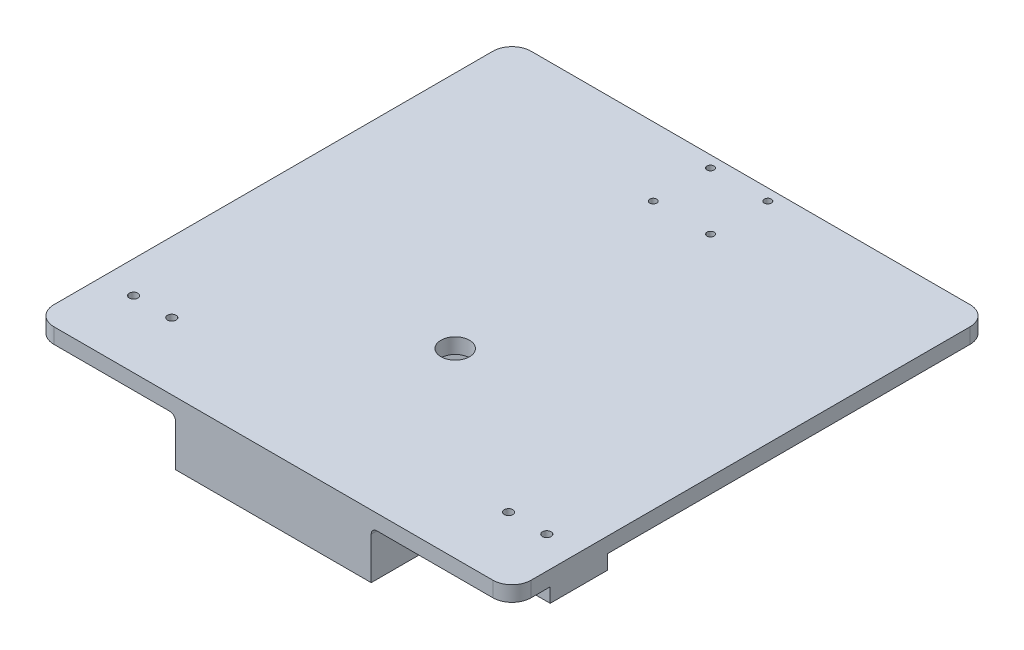
SolidWorks part; units mm, degrees
ref_plane "Front Plane" through (0, 0, 0) normal (0, 0, 1) x (1, 0, 0)
ref_plane "Top Plane" through (0, 0, 0) normal (0, 1, 0) x (1, 0, 0)
ref_plane "Right Plane" through (0, 0, 0) normal (1, 0, 0) x (0, 0, -1)
sketch "Sketch1" plane through (0, 0, 0) normal (0, 1, 0) x (1, 0, 0)
  line L1 (-125, 125) -> (125, 125)
  line L2 (-125, 125) -> (-125, -125)
  line L3 (-125, -125) -> (125, -125)
  line L4 (125, 125) -> (125, -125)
  line L5 (-125, 125) -> (125, -125) construction
  line L6 (-125, -125) -> (125, 125) construction
  point P0 (0, 0)
  dimension "D1" = 250
  dimension "D2" = 250
extrude "Boss-Extrude1" add sketch "Sketch1" along normal blind 8
sketch "Sketch2" plane through (0, 0, 0) normal (0, -1, 0) x (1, 0, 0)
  line L0 (-125, -125) -> (-125, 125) construction
  line L1 (-71.45, 75) -> (-125, 75)
  line L2 (-71.45, 75) -> (-71.45, 105)
  line L3 (-71.45, 105) -> (-125, 105)
  line L4 (-125, 75) -> (-125, 105)
  line L5 (-125, 105) -> (-119, 105) construction
  line L6 (125, 125) -> (125, -125) construction
  line L7 (71.45, 105) -> (125, 105)
  line L8 (71.45, 105) -> (71.45, 75)
  line L9 (71.45, 75) -> (125, 75)
  line L10 (125, 105) -> (125, 75)
  point P16 (0, 0)
  point P17 (71.45, 75)
extrude "Boss-Extrude2" add sketch "Sketch2" along normal up to surface (7.5 mm away)
sketch "Sketch3" plane through (0, -7.5, 0) normal (0, -1, 0) x (1, 0, 0)
  circle A0 centre (108.225, 90) radius 2.25
  circle A1 centre (88.225, 90) radius 2.25
  circle A2 centre (-108.225, 90) radius 2.25
  circle A3 centre (-88.225, 90) radius 2.25
extrude "Cut-Extrude1" cut sketch "Sketch3" against normal through all
sketch "Sketch4" plane through (0, 0, 0) normal (0, -1, 0) x (1, 0, 0)
  line L0 (0, 125) -> (-51.25, 125)
  line L1 (-48.25, 19.74) -> (0, 19.74) construction
  line L2 (-125, 125) -> (125, 125) construction
  line L3 (0, 122) -> (-48.25, 122) construction
  line L4 (-51.25, 125) -> (-51.25, 16.74)
  line L5 (-51.25, 16.74) -> (0, 16.74)
  line L8 (0, 125) -> (0, -101.2984) construction
  line L9 (-36.25, 112) -> (-36.25, 41.74) construction
  line L10 (-36.25, 41.74) -> (-2.5, 41.74) construction
  line L11 (0, 122) -> (-40.25, 122)
  line L12 (-48.25, 114) -> (-48.25, 27.74)
  line L13 (-40.25, 19.74) -> (0, 19.74)
  line L14 (0, 125) -> (0, -43.5626) construction
  line L15 (40.25, 19.74) -> (0, 19.74)
  line L16 (51.25, 16.74) -> (0, 16.74)
  line L17 (48.25, 114) -> (48.25, 27.74)
  line L18 (0, 122) -> (40.25, 122)
  line L19 (51.25, 125) -> (51.25, 16.74)
  line L20 (0, 125) -> (51.25, 125)
  line L21 (48.25, 70.87) -> (-48.25, 70.87) construction
  line L24 (48.25, 114) -> (40.25, 114)
  line L25 (40.25, 122) -> (40.25, 114)
  line L28 (-48.25, 114) -> (-40.25, 114)
  line L29 (-40.25, 122) -> (-40.25, 114)
  line L32 (-48.25, 27.74) -> (-40.25, 27.74)
  line L33 (-40.25, 19.74) -> (-40.25, 27.74)
  line L36 (48.25, 27.74) -> (40.25, 27.74)
  line L37 (40.25, 19.74) -> (40.25, 27.74)
  line L38 (-48.25, 122) -> (-48.25, 19.74) construction
  circle A0 centre (-44.25, 118) radius 1.5
  circle A1 centre (44.25, 118) radius 1.5
  circle A2 centre (44.25, 23.74) radius 1.5
  circle A3 centre (-44.25, 23.74) radius 1.5
  dimension "D12" = 3
  dimension "D2" = 25
  dimension "D3" = 3
  dimension "D1" = 15
  dimension "D4" = 8
  dimension "D5" = 8
  dimension "D6" = 8
  dimension "D7" = 8
  dimension "D8" = 8
  dimension "D9" = 8
  dimension "D10" = 8
  dimension "D11" = 8
extrude "Boss-Extrude3" add sketch "Sketch4" along normal blind 25
fillet "Fillet1" radius 3 5 edges at (51.25, -12.5, 16.74) (-51.25, -12.5, 16.74) (0, 0, 16.74) (51.25, 0, 70.87) (-51.25, 0, 70.87)
sketch "Sketch5" plane through (-51.25, 0, 0) normal (-1, 0, 0) x (0, 0, 1)
  line L0 (72.37, -3) -> (72.37, -25) construction
  line L1 (125, -3) -> (19.74, -3) construction
  line L2 (125, -25) -> (19.74, -25) construction
  line L4 (82.37, -3) -> (62.37, -3)
  line L5 (82.37, -3) -> (82.37, -13)
  line L6 (82.37, -13) -> (62.37, -13)
  line L7 (62.37, -3) -> (62.37, -13)
  dimension "D1" = 20
  dimension "D2" = 10
  dimension "D3" = 10
extrude "Cut-Extrude2" cut sketch "Sketch5" against normal up to surface (102.5 mm away) up to face at (51.25, -14, 72.37)
sketch "Sketch6" plane through (0, 0, 0) normal (0, -1, 0) x (1, 0, 0)
  line L0 (0, 125) -> (0, -101.2984) construction
  line L1 (-40.25, 19.74) -> (40.25, 19.74) construction
  circle A0 centre (-15, -89) radius 1.851
  circle A1 centre (15, -89) radius 1.851
  circle A2 centre (15, -119) radius 1.851
  circle A3 centre (-15, -119) radius 1.851
  circle A4 centre (0, 29.74) radius 7.5
  dimension "D2" = 15
  dimension "D1" = 10
extrude "Cut-Extrude3" cut sketch "Sketch6" against normal blind 20
fillet "Fillet2" radius 10 4 edges at (-125, 4, -125) (125, 4, -125) (125, 4, 125) (-125, 4, 125)
